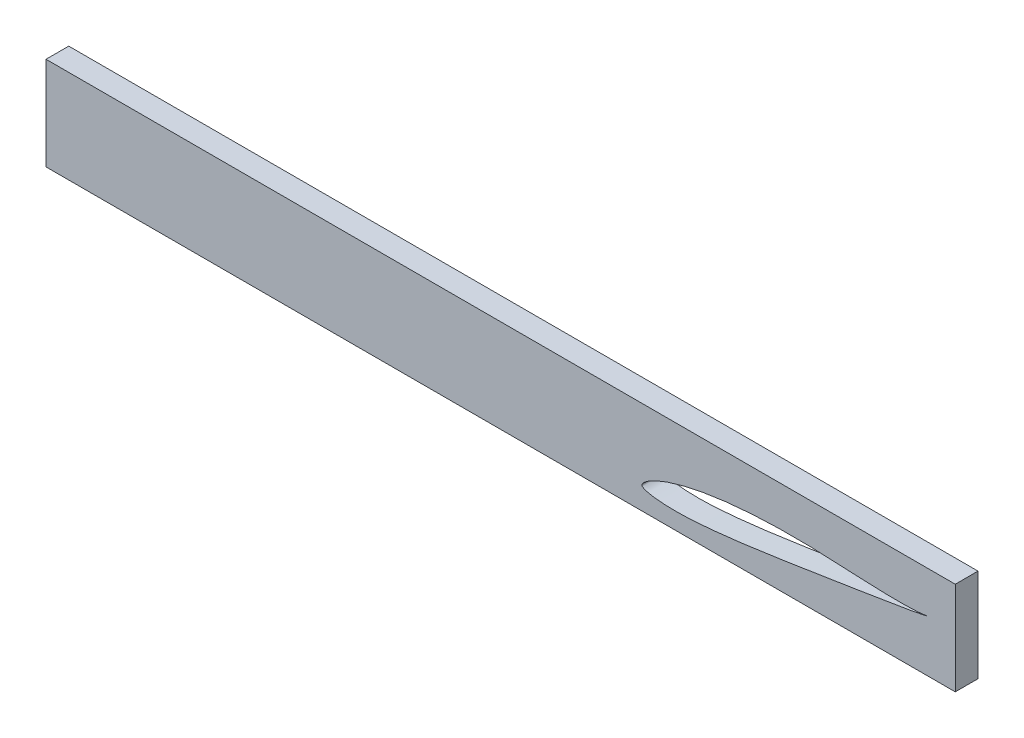
SolidWorks part; units mm, degrees
ref_plane "Ebene vorne" through (0, 0, 0) normal (0, 0, 1) x (1, 0, 0)
ref_plane "Ebene oben" through (0, 0, 0) normal (0, 1, 0) x (1, 0, 0)
ref_plane "Ebene rechts" through (0, 0, 0) normal (1, 0, 0) x (0, 0, -1)
sketch "Sketch1" plane through (0, 0, 200) normal (0, 0, 1) x (1, 0, 0)
  line L1 (-15.4558, 10.6915) -> (144.4824, 10.6915)
  line L2 (-15.4558, 10.6915) -> (-15.4558, -5.7093)
  line L3 (-15.4558, -5.7093) -> (144.4824, -5.7093)
  line L4 (144.4824, 10.6915) -> (144.4824, -5.7093)
  spline S0 degree 3 poles (139.4845, 3.3236) (139.8974, 3.4191) (139.4418, 3.335) (139.0638, 3.2922) (138.1307, 3.1971) (136.9874, 3.1384) (135.5047, 3.093) (133.7779, 3.089) (131.8221, 3.1262) (129.685, 3.2011) (127.4034, 3.3047) (125.0163, 3.4254) (122.5578, 3.5467) (120.0558, 3.6442) (117.5326, 3.7017) (115.0073, 3.7112) (112.4993, 3.6668) (110.0286, 3.5677) (107.6159, 3.4137) (105.2824, 3.2067) (103.0491, 2.9486) (100.9356, 2.6401) (98.9593, 2.2847) (97.1355, 1.8858) (95.4777, 1.4505) (93.9978, 0.991) (92.7077, 0.5176) (91.6187, 0.0404) (90.7381, -0.4291) (90.0724, -0.8777) (89.6622, -1.2494) (89.4709, -1.5086) (89.402, -1.6435) (89.3736, -1.7282) (89.3635, -1.7944) (89.3682, -1.8461) (89.395, -1.8918) (89.4441, -1.9436) (89.5218, -2.0031) (89.6584, -2.0841) (89.9779, -2.2325) (90.5714, -2.4019) (91.4699, -2.5662) (92.5998, -2.6906) (93.9484, -2.7658) (95.5047, -2.7837) (97.2563, -2.7392) (99.19, -2.6325) (101.2904, -2.4638) (103.54, -2.2373) (105.9189, -1.9579) (108.4052, -1.6346) (110.9736, -1.2755) (113.5965, -0.8917) (116.244, -0.4916) (118.8849, -0.0845) (121.4872, 0.3226) (124.0194, 0.7224) (126.4507, 1.1098) (128.7514, 1.4788) (130.8937, 1.8256) (132.8507, 2.1442) (134.5999, 2.4326) (136.1132, 2.6856) (137.3896, 2.9067) (138.3645, 3.0818) (139.1535, 3.2418) (139.4845, 3.3236) (139.8974, 3.4191) (139.4418, 3.335) knots -0.013312 -0.00609 -0.00158 0 0.001669 0.006747 0.015187 0.026742 0.041155 0.058129 0.077283 0.098227 0.12058 0.143966 0.168018 0.192451 0.217075 0.24171 0.266182 0.29031 0.313903 0.336767 0.358704 0.37954 0.399122 0.417322 0.434037 0.449154 0.462553 0.474139 0.483848 0.491647 0.497539 0.499898 0.501005 0.501951 0.502492 0.502956 0.503431 0.504004 0.505035 0.506276 0.508636 0.515301 0.524213 0.535296 0.548467 0.563638 0.580726 0.599619 0.62018 0.642246 0.665633 0.690118 0.715452 0.741354 0.76752 0.793634 0.819375 0.844429 0.868488 0.891259 0.912467 0.93185 0.949165 0.964196 0.976755 0.986688 0.99391 0.99842 1 1.001669 1.006747 1.015187 only from (139.8097, 3.4008) to (139.8097, 3.4008) construction
  spline S1 degree 3 poles (139.4845, 3.3236) (139.8974, 3.4191) (139.4418, 3.335) (139.0638, 3.2922) (138.1307, 3.1971) (136.9874, 3.1384) (135.5047, 3.093) (133.7779, 3.089) (131.8221, 3.1262) (129.685, 3.2011) (127.4034, 3.3047) (125.0163, 3.4254) (122.5578, 3.5467) (120.0558, 3.6442) (117.5326, 3.7017) (115.0073, 3.7112) (112.4993, 3.6668) (110.0286, 3.5677) (107.6159, 3.4137) (105.2824, 3.2067) (103.0491, 2.9486) (100.9356, 2.6401) (98.9593, 2.2847) (97.1355, 1.8858) (95.4777, 1.4505) (93.9978, 0.991) (92.7077, 0.5176) (91.6187, 0.0404) (90.7381, -0.4291) (90.0724, -0.8777) (89.6622, -1.2494) (89.4709, -1.5086) (89.402, -1.6435) (89.3736, -1.7282) (89.3635, -1.7944) (89.3682, -1.8461) (89.395, -1.8918) (89.4441, -1.9436) (89.5218, -2.0031) (89.6584, -2.0841) (89.9779, -2.2325) (90.5714, -2.4019) (91.4699, -2.5662) (92.5998, -2.6906) (93.9484, -2.7658) (95.5047, -2.7837) (97.2563, -2.7392) (99.19, -2.6325) (101.2904, -2.4638) (103.54, -2.2373) (105.9189, -1.9579) (108.4052, -1.6346) (110.9736, -1.2755) (113.5965, -0.8917) (116.244, -0.4916) (118.8849, -0.0845) (121.4872, 0.3226) (124.0194, 0.7224) (126.4507, 1.1098) (128.7514, 1.4788) (130.8937, 1.8256) (132.8507, 2.1442) (134.5999, 2.4326) (136.1132, 2.6856) (137.3896, 2.9067) (138.3645, 3.0818) (139.1535, 3.2418) (139.4845, 3.3236) (139.8974, 3.4191) (139.4418, 3.335) knots -0.013312 -0.00609 -0.00158 0 0.001669 0.006747 0.015187 0.026742 0.041155 0.058129 0.077283 0.098227 0.12058 0.143966 0.168018 0.192451 0.217075 0.24171 0.266182 0.29031 0.313903 0.336767 0.358704 0.37954 0.399122 0.417322 0.434037 0.449154 0.462553 0.474139 0.483848 0.491647 0.497539 0.499898 0.501005 0.501951 0.502492 0.502956 0.503431 0.504004 0.505035 0.506276 0.508636 0.515301 0.524213 0.535296 0.548467 0.563638 0.580726 0.599619 0.62018 0.642246 0.665633 0.690118 0.715452 0.741354 0.76752 0.793634 0.819375 0.844429 0.868488 0.891259 0.912467 0.93185 0.949165 0.964196 0.976755 0.986688 0.99391 0.99842 1 1.001669 1.006747 1.015187 only from (139.8097, 3.4008) to (139.8097, 3.4008)
extrude "Boss-Extrude1" add sketch "Sketch1" along normal blind 4
